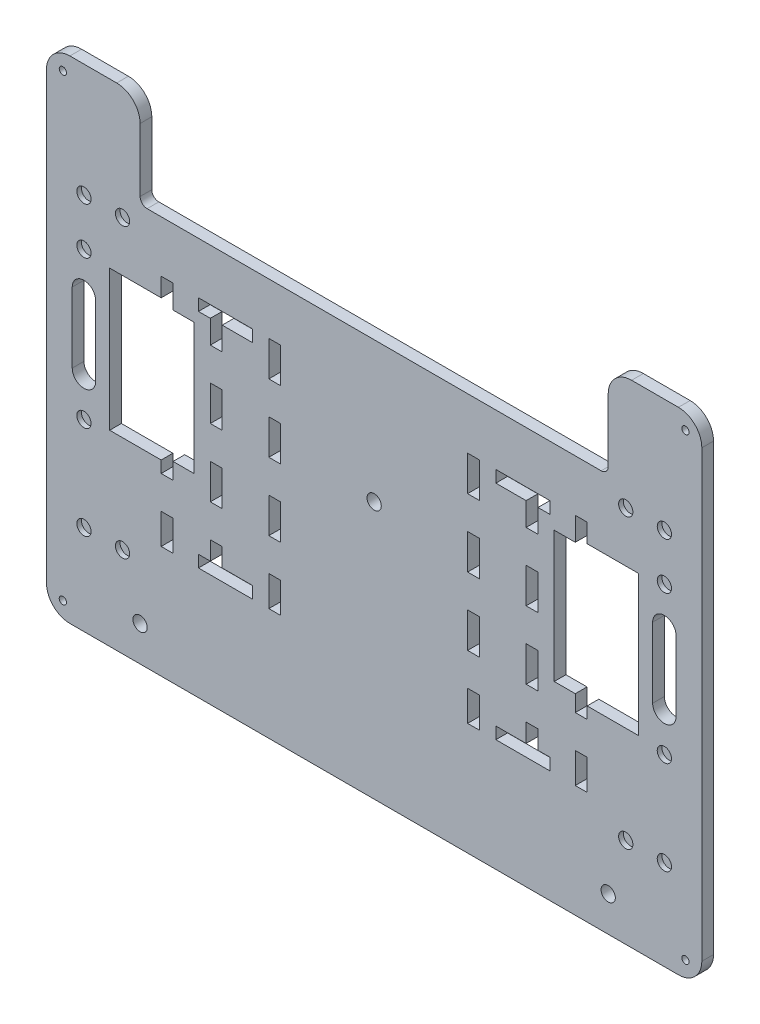
SolidWorks part; units mm, degrees
material "Acrylique (impact moyen-haut)"
ref_plane "Plan de face" through (0, 0, 0) normal (0, 0, 1) x (1, 0, 0)
ref_plane "Plan de dessus" through (0, 0, 0) normal (0, 1, 0) x (1, 0, 0)
ref_plane "Plan de droite" through (0, 0, 0) normal (1, 0, 0) x (0, 0, -1)
sketch "Esquisse1" plane through (0, 0, 0) normal (0, 0, 1) x (1, 0, 0)
  line L1 (130, -105) -> (-130, -105)
  line L2 (140, -95) -> (140, 105)
  line L3 (140, 105) -> (-140, 105)
  line L4 (-140, -95) -> (-140, 105)
  line L5 (140, -105) -> (-140, 105) construction
  line L6 (140, 105) -> (-140, -105) construction
  arc A0 (130, -105) -> (140, -95) centre (130, -95) ccw
  arc A1 (-130, -105) -> (-140, -95) centre (-130, -95) cw
  point P0 (0, 0)
  dimension "D3" = 10
  dimension "D1" = 210
  dimension "D2" = 280
extrude "Boss.-Extru.1" add sketch "Esquisse1" along normal blind 5
sketch "Esquisse2" plane through (0, 0, 5) normal (0, 0, 1) x (1, 0, 0)
  line L0 (-85.93, -1) -> (-91, -1)
  line L1 (-85.93, 28) -> (-91, 28)
  line L2 (-85.93, 28) -> (-85.93, 43)
  line L3 (-85.93, 43) -> (-91, 43)
  line L4 (-91, 28) -> (-91, 43)
  line L5 (-85.93, 28) -> (-91, 43) construction
  line L6 (-85.93, 43) -> (-91, 28) construction
  line L7 (-85.93, -1) -> (-85.93, 14)
  line L8 (-85.93, 14) -> (-91, 14)
  line L9 (-91, -1) -> (-91, 14)
  line L10 (-85.93, -1) -> (-91, 14) construction
  line L11 (-85.93, 14) -> (-91, -1) construction
  line L12 (-85.93, -57) -> (-91, -57)
  line L13 (-85.93, -30) -> (-91, -30)
  line L14 (-85.93, -30) -> (-85.93, -15)
  line L15 (-85.93, -15) -> (-91, -15)
  line L16 (-91, -30) -> (-91, -15)
  line L17 (-85.93, -30) -> (-91, -15) construction
  line L18 (-85.93, -15) -> (-91, -30) construction
  line L19 (-85.93, -57) -> (-85.93, -44)
  line L20 (-85.93, -44) -> (-91, -44)
  line L21 (-91, -57) -> (-91, -44)
  line L22 (-85.93, -57) -> (-91, -44) construction
  line L23 (-85.93, -44) -> (-91, -57) construction
  line L26 (-64.93, -1) -> (-70, -1)
  line L27 (-64.93, 28) -> (-70, 28)
  line L28 (-64.93, 28) -> (-64.93, 43)
  line L29 (-64.93, 43) -> (-70, 43)
  line L30 (-70, 28) -> (-70, 43)
  line L31 (-64.93, 28) -> (-70, 43) construction
  line L32 (-64.93, 43) -> (-70, 28) construction
  line L33 (-64.93, -1) -> (-64.93, 14)
  line L34 (-64.93, 14) -> (-70, 14)
  line L35 (-70, -1) -> (-70, 14)
  line L36 (-64.93, -1) -> (-70, 14) construction
  line L37 (-64.93, 14) -> (-70, -1) construction
  line L38 (-64.93, -57) -> (-70, -57)
  line L39 (-64.93, -30) -> (-70, -30)
  line L40 (-64.93, -30) -> (-64.93, -15)
  line L41 (-64.93, -15) -> (-70, -15)
  line L42 (-70, -30) -> (-70, -15)
  line L43 (-64.93, -30) -> (-70, -15) construction
  line L44 (-64.93, -15) -> (-70, -30) construction
  line L45 (-64.93, -57) -> (-64.93, -44)
  line L46 (-64.93, -44) -> (-70, -44)
  line L47 (-70, -57) -> (-70, -44)
  line L48 (-64.93, -57) -> (-70, -44) construction
  line L49 (-64.93, -44) -> (-70, -57) construction
  line L50 (-39.93, -1) -> (-45, -1)
  line L51 (-39.93, 28) -> (-45, 28)
  line L52 (-39.93, 28) -> (-39.93, 43)
  line L53 (-39.93, 43) -> (-45, 43)
  line L54 (-45, 28) -> (-45, 43)
  line L55 (-39.93, 28) -> (-45, 43) construction
  line L56 (-39.93, 43) -> (-45, 28) construction
  line L57 (-39.93, -1) -> (-39.93, 14)
  line L58 (-39.93, 14) -> (-45, 14)
  line L59 (-45, -1) -> (-45, 14)
  line L60 (-39.93, -1) -> (-45, 14) construction
  line L61 (-39.93, 14) -> (-45, -1) construction
  line L62 (-39.93, -57) -> (-45, -57)
  line L63 (-39.93, -30) -> (-45, -30)
  line L64 (-39.93, -30) -> (-39.93, -15)
  line L65 (-39.93, -15) -> (-45, -15)
  line L66 (-45, -30) -> (-45, -15)
  line L67 (-39.93, -30) -> (-45, -15) construction
  line L68 (-39.93, -15) -> (-45, -30) construction
  line L69 (-39.93, -57) -> (-39.93, -44)
  line L70 (-39.93, -44) -> (-45, -44)
  line L71 (-45, -57) -> (-45, -44)
  line L72 (-39.93, -57) -> (-45, -44) construction
  line L73 (-39.93, -44) -> (-45, -57) construction
  line L74 (0, 0) -> (0, 77.3847) construction
  line L75 (-75.07, 43) -> (-52, 43)
  line L76 (-75.07, 43) -> (-75.07, 37.93)
  line L77 (-75.07, 37.93) -> (-52, 37.93)
  line L78 (-52, 43) -> (-52, 37.93)
  line L79 (-75.07, -57) -> (-52, -57)
  line L80 (-75.07, -57) -> (-75.07, -51.93)
  line L81 (-75.07, -51.93) -> (-52, -51.93)
  line L82 (-52, -57) -> (-52, -51.93)
  line L83 (39.93, -44) -> (45, -57) construction
  line L84 (39.93, -57) -> (45, -44) construction
  line L85 (39.93, -15) -> (45, -30) construction
  line L86 (39.93, -30) -> (45, -15) construction
  line L87 (39.93, 14) -> (45, -1) construction
  line L88 (39.93, -1) -> (45, 14) construction
  line L89 (39.93, 43) -> (45, 28) construction
  line L90 (39.93, 28) -> (45, 43) construction
  line L91 (64.93, -44) -> (70, -57) construction
  line L92 (64.93, -57) -> (70, -44) construction
  line L93 (64.93, -15) -> (70, -30) construction
  line L94 (64.93, -30) -> (70, -15) construction
  line L95 (64.93, 14) -> (70, -1) construction
  line L96 (64.93, -1) -> (70, 14) construction
  line L97 (64.93, 43) -> (70, 28) construction
  line L98 (64.93, 28) -> (70, 43) construction
  line L99 (85.93, -44) -> (91, -57) construction
  line L100 (85.93, -57) -> (91, -44) construction
  line L101 (85.93, -15) -> (91, -30) construction
  line L102 (85.93, -30) -> (91, -15) construction
  line L103 (85.93, 14) -> (91, -1) construction
  line L104 (85.93, -1) -> (91, 14) construction
  line L105 (85.93, 43) -> (91, 28) construction
  line L106 (85.93, 28) -> (91, 43) construction
  line L107 (52, -57) -> (52, -51.93)
  line L108 (75.07, -51.93) -> (52, -51.93)
  line L109 (75.07, -57) -> (75.07, -51.93)
  line L110 (75.07, -57) -> (52, -57)
  line L111 (52, 43) -> (52, 37.93)
  line L112 (75.07, 37.93) -> (52, 37.93)
  line L113 (75.07, 43) -> (75.07, 37.93)
  line L114 (75.07, 43) -> (52, 43)
  line L115 (45, -57) -> (45, -44)
  line L116 (39.93, -44) -> (45, -44)
  line L117 (39.93, -57) -> (39.93, -44)
  line L118 (45, -30) -> (45, -15)
  line L119 (39.93, -15) -> (45, -15)
  line L120 (39.93, -30) -> (39.93, -15)
  line L121 (39.93, -30) -> (45, -30)
  line L122 (39.93, -57) -> (45, -57)
  line L123 (45, -1) -> (45, 14)
  line L124 (39.93, 14) -> (45, 14)
  line L125 (39.93, -1) -> (39.93, 14)
  line L126 (45, 28) -> (45, 43)
  line L127 (39.93, 43) -> (45, 43)
  line L128 (39.93, 28) -> (39.93, 43)
  line L129 (39.93, 28) -> (45, 28)
  line L130 (39.93, -1) -> (45, -1)
  line L131 (70, -57) -> (70, -44)
  line L132 (64.93, -44) -> (70, -44)
  line L133 (64.93, -57) -> (64.93, -44)
  line L134 (70, -30) -> (70, -15)
  line L135 (64.93, -15) -> (70, -15)
  line L136 (64.93, -30) -> (64.93, -15)
  line L137 (64.93, -30) -> (70, -30)
  line L138 (64.93, -57) -> (70, -57)
  line L139 (70, -1) -> (70, 14)
  line L140 (64.93, 14) -> (70, 14)
  line L141 (64.93, -1) -> (64.93, 14)
  line L142 (70, 28) -> (70, 43)
  line L143 (64.93, 43) -> (70, 43)
  line L144 (64.93, 28) -> (64.93, 43)
  line L145 (64.93, 28) -> (70, 28)
  line L146 (64.93, -1) -> (70, -1)
  line L147 (91, -57) -> (91, -44)
  line L148 (85.93, -44) -> (91, -44)
  line L149 (85.93, -57) -> (85.93, -44)
  line L150 (91, -30) -> (91, -15)
  line L151 (85.93, -15) -> (91, -15)
  line L152 (85.93, -30) -> (85.93, -15)
  line L153 (85.93, -30) -> (91, -30)
  line L154 (85.93, -57) -> (91, -57)
  line L155 (91, -1) -> (91, 14)
  line L156 (85.93, 14) -> (91, 14)
  line L157 (85.93, -1) -> (85.93, 14)
  line L158 (91, 28) -> (91, 43)
  line L159 (85.93, 43) -> (91, 43)
  line L160 (85.93, 28) -> (85.93, 43)
  line L161 (85.93, 28) -> (91, 28)
  line L162 (85.93, -1) -> (91, -1)
  line L163 (76.93, -23) -> (85.93, 33) construction
  line L164 (-91, -25) -> (-113, -25)
  line L165 (-91, -25) -> (-91, 35)
  line L166 (-91, 35) -> (-113, 35)
  line L167 (-113, -25) -> (-113, 35)
  line L168 (-91, -25) -> (-113, 35) construction
  line L169 (-91, 35) -> (-113, -25) construction
  line L170 (-76.93, -23) -> (-85.93, -23)
  line L171 (-76.93, -23) -> (-76.93, 33)
  line L172 (-76.93, 33) -> (-85.93, 33)
  line L173 (-85.93, -23) -> (-85.93, 33)
  line L174 (-76.93, -23) -> (-85.93, 33) construction
  line L175 (-76.93, 33) -> (-85.93, -23) construction
  line L176 (76.93, 33) -> (85.93, -23) construction
  line L177 (91, 35) -> (113, -25) construction
  line L178 (91, -25) -> (113, 35) construction
  line L179 (91, 35) -> (113, 35)
  line L180 (113, -25) -> (113, 35)
  line L181 (91, -25) -> (113, -25)
  line L182 (91, -25) -> (91, 35)
  line L183 (85.93, -23) -> (85.93, 33)
  line L184 (76.93, -23) -> (85.93, -23)
  line L185 (76.93, -23) -> (76.93, 33)
  line L186 (76.93, 33) -> (85.93, 33)
  line L187 (140, 105) -> (-140, 105) construction
  line L188 (-140, 105) -> (-140, -95) construction
  point P0 (-88.465, 35.5)
  point P5 (-88.465, 6.5)
  point P10 (-88.465, -22.5)
  point P15 (-88.465, -50.5)
  point P24 (-67.465, 35.5)
  point P29 (-67.465, 6.5)
  point P34 (-67.465, -22.5)
  point P39 (-67.465, -50.5)
  point P44 (-42.465, 35.5)
  point P49 (-42.465, 6.5)
  point P54 (-42.465, -22.5)
  point P59 (-42.465, -50.5)
  point P131 (42.465, -50.5)
  point P132 (42.465, -22.5)
  point P133 (42.465, 6.5)
  point P134 (42.465, 35.5)
  point P135 (67.465, -50.5)
  point P136 (67.465, -22.5)
  point P137 (67.465, 6.5)
  point P138 (67.465, 35.5)
  point P139 (88.465, -50.5)
  point P140 (88.465, -22.5)
  point P141 (88.465, 6.5)
  point P142 (88.465, 35.5)
  point P143 (-102, 5)
  point P148 (-81.43, 5)
  point P153 (81.43, 5)
  point P158 (102, 5)
  dimension "D1" = 5.07
  dimension "D2" = 15
  dimension "D3" = 5.07
  dimension "D4" = 14
  dimension "D5" = 0
  dimension "D6" = 15
  dimension "D7" = 5.07
  dimension "D8" = 15
  dimension "D9" = 5.07
  dimension "D10" = 14
  dimension "D11" = 0
  dimension "D12" = 100
  dimension "D13" = 14
  dimension "D14" = 0
  dimension "D15" = 100
  dimension "D16" = 27
  dimension "D17" = 5.07
  dimension "D18" = 15
  dimension "D19" = 5.07
  dimension "D20" = 14
  dimension "D21" = 0
  dimension "D22" = 15
  dimension "D23" = 5.07
  dimension "D24" = 15
  dimension "D25" = 5.07
  dimension "D26" = 14
  dimension "D27" = 0
  dimension "D28" = 14
  dimension "D29" = 0
  dimension "D30" = 100
  dimension "D31" = 0
  dimension "D32" = 46
  dimension "D33" = 5.07
  dimension "D34" = 15
  dimension "D35" = 5.07
  dimension "D36" = 14
  dimension "D37" = 0
  dimension "D38" = 15
  dimension "D39" = 5.07
  dimension "D40" = 15
  dimension "D41" = 5.07
  dimension "D42" = 14
  dimension "D43" = 0
  dimension "D44" = 14
  dimension "D45" = 0
  dimension "D46" = 100
  dimension "D47" = 0
  dimension "D48" = 25
  dimension "D49" = 23.07
  dimension "D50" = 15.93
  dimension "D51" = 5.07
  dimension "D52" = 5.07
  dimension "D53" = 23.07
  dimension "D54" = 5.07
  dimension "D55" = 5.07
  dimension "D56" = 15.93
  dimension "D57" = 0
  dimension "D58" = 60
  dimension "D59" = 22
  dimension "D60" = 38
  dimension "D61" = 38
  dimension "D62" = 56
  dimension "D63" = 0
  dimension "D64" = 9
extrude "Enlèv. mat.-Extru.1" cut sketch "Esquisse2" against normal blind 10 contours L183 L156 L182 L161 | L186 L185 L184 L152 L183 L157 L160 | L160 L161 L158 L159 | L182 L150 L181 L180 L179 L158 L155 | L157 L162 L155 L156 | L152 L153 L150 L151 | L183 L151 L182 L162 | L131 L110 L109 L108 | L133 L110 L131 L108 | L110 L133 L108 L107 | L149 L154 L147 L148 | L167 L164 L16 L165 L9 L4 L166 | L9 L0 L7 L8 | L8 L173 L1 L165 | L15 L173 L0 L165 | L77 L30 L27 L28 | L116 L115 L122 L117 | L121 L118 L119 L120 | L137 L134 L135 L136 | L141 L140 L139 L146 | L123 L124 L125 L130 | L129 L126 L127 L128 | L144 L143 L142 L145 | L112 L111 L114 L113 | L20 L21 L12 L19 | L81 L82 L79 L80 | L47 L46 L45 L38 | L71 L70 L69 L62 | L66 L65 L64 L63 | L39 L42 L41 L40 | L26 L35 L34 L33 | L50 L59 L58 L57 | L51 L54 L53 L52
sketch "Esquisse3" plane through (0, 0, 5) normal (0, 0, 1) x (1, 0, 0)
  line L0 (-124, 5) -> (-31.3779, 5) construction
  line L1 (-113, -25) -> (-113, 35) construction
  line L3 (-124, 36.5) -> (-124, -26.5) construction
  line L4 (-140, 105) -> (-140, -95) construction
  line L5 (0, 0) -> (0, 65.434) construction
  line L6 (124, 36.5) -> (124, -26.5) construction
  circle A0 centre (-124, -26.5) radius 3.05
  circle A1 centre (-124, 36.5) radius 3.05
  circle A2 centre (124, 36.5) radius 3.05
  circle A3 centre (124, -26.5) radius 3.05
  circle A4 centre (-124, 56.5) radius 3.05
  circle A5 centre (-107.5, 56.5) radius 3.05
  circle A6 centre (-124, -66.5) radius 3.05
  circle A7 centre (-107.5, -66.5) radius 3.05
  circle A8 centre (107.5, -66.5) radius 3.05
  circle A9 centre (124, -66.5) radius 3.05
  circle A10 centre (107.5, 56.5) radius 3.05
  circle A11 centre (124, 56.5) radius 3.05
  point P4 (-113, 5)
  point P5 (-124, 5)
  point P17 (124, 5)
  point P18 (113, 5)
  dimension "D1" = 6.1
  dimension "D4" = 6.1
  dimension "D6" = 6.1
  dimension "D8" = 6.1
  dimension "D10" = 6.1
  dimension "D2" = 63
  dimension "D3" = 16
  dimension "D5" = 20
  dimension "D7" = 16.5
  dimension "D9" = 40
  dimension "D11" = 16.5
extrude "Enlèv. mat.-Extru.2" cut sketch "Esquisse3" against normal blind 2
sketch "Esquisse4" plane through (0, 0, 5) normal (0, 0, 1) x (1, 0, 0)
  line L0 (-124, 20) -> (-124, -10) construction
  line L1 (-119, 20) -> (-119, -10)
  line L2 (-129, 20) -> (-129, -10)
  line L3 (-124, 36.5) -> (-124, -26.5) construction
  line L4 (0, 0) -> (0, 61.7257) construction
  line L5 (124, 36.5) -> (124, -26.5) construction
  line L6 (124, 20) -> (124, -10) construction
  line L7 (119, 20) -> (119, -10)
  line L8 (129, 20) -> (129, -10)
  line L9 (-110, 105) -> (110, 105)
  line L11 (-100, 95) -> (-100, 68)
  line L12 (-97, 65) -> (97, 65)
  line L14 (140, 105) -> (130, 105)
  line L15 (140, 95) -> (140, 105)
  line L16 (-140, 95) -> (-140, 105)
  line L17 (100, 95) -> (100, 68)
  line L18 (-140, 105) -> (-130, 105)
  arc A0 (-119, 20) -> (-129, 20) centre (-124, 20) ccw
  arc A1 (-129, -10) -> (-119, -10) centre (-124, -10) ccw
  arc A2 (119, 20) -> (129, 20) centre (124, 20) cw
  arc A3 (129, -10) -> (119, -10) centre (124, -10) cw
  arc A4 (-100, 95) -> (-110, 105) centre (-110, 95) ccw
  arc A5 (-140, 95) -> (-130, 105) centre (-130, 95) cw
  arc A6 (-100, 68) -> (-97, 65) centre (-97, 68) ccw
  arc A7 (100, 68) -> (97, 65) centre (97, 68) cw
  arc A8 (140, 95) -> (130, 105) centre (130, 95) ccw
  arc A9 (100, 95) -> (110, 105) centre (110, 95) cw
  point P2 (-124, 5)
  point P18 (124, 5)
  point P40 (-140, 105)
  point P43 (-100, 65)
  point P50 (100, 65)
  dimension "D4" = 10
  dimension "D5" = 10
  dimension "D6" = 3
  dimension "D1" = 10
  dimension "D2" = 30
  dimension "D3" = 194
  dimension "D7" = 40
  dimension "D8" = 220
extrude "Enlèv. mat.-Extru.3" cut sketch "Esquisse4" against normal through all
sketch "Esquisse5" plane through (0, 0, 5) normal (0, 0, 1) x (1, 0, 0)
  line L0 (-119, 5) -> (119, 5) construction
  line L1 (-119, -10) -> (-119, 20) construction
  line L2 (119, 20) -> (119, -10) construction
  line L3 (-140, 95) -> (-140, -95) construction
  line L4 (-110, 105) -> (-130, 105) construction
  line L5 (-130, -105) -> (130, -105) construction
  line L6 (0, 5) -> (0, 82.0623) construction
  circle A0 centre (0, 5) radius 3.05
  circle A1 centre (-133, 98) radius 1.55
  circle A2 centre (-100, -90) radius 3.05
  circle A3 centre (-133, -98) radius 1.55
  circle A4 centre (133, -98) radius 1.55
  circle A5 centre (100, -90) radius 3.05
  circle A6 centre (133, 98) radius 1.55
  point P6 (0, 5)
  dimension "D1" = 6.1
  dimension "D2" = 3.1
  dimension "D5" = 6.1
  dimension "D8" = 3.1
  dimension "D9" = 7
  dimension "D3" = 7
  dimension "D4" = 7
  dimension "D6" = 40
  dimension "D7" = 15
  dimension "D10" = 7
extrude "Enlèv. mat.-Extru.4" cut sketch "Esquisse5" against normal through all
